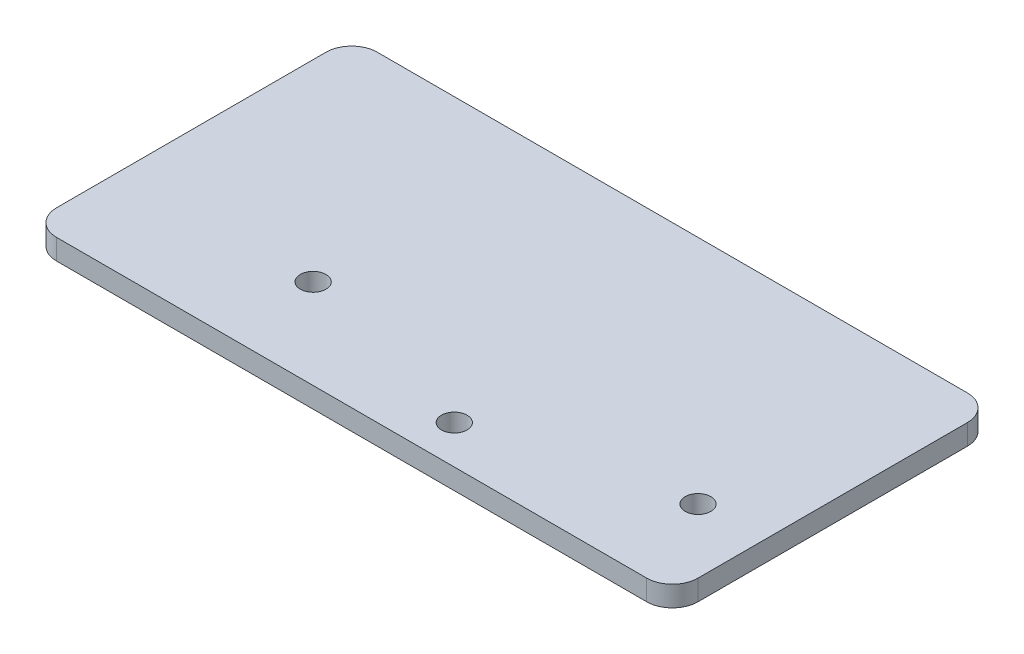
SolidWorks part; units mm, degrees
material "A-玻璃纤维"
ref_plane "前视基准面" through (0, 0, 0) normal (0, 0, 1) x (1, 0, 0)
ref_plane "上视基准面" through (0, 0, 0) normal (0, 1, 0) x (1, 0, 0)
ref_plane "右视基准面" through (0, 0, 0) normal (1, 0, 0) x (0, 0, -1)
other "Configuration Table"
sketch "草图1" plane through (0, 0, 0) normal (0, 1, 0) x (1, 0, 0)
  line L0 (-10, -5.5) -> (38.4981, -5.5) construction
  line L1 (-25, -12.5) -> (25, -12.5)
  line L2 (-25, -12.5) -> (-25, 12.5)
  line L3 (-25, 12.5) -> (25, 12.5)
  line L4 (25, -12.5) -> (25, 12.5)
  line L5 (-25, -12.5) -> (25, 12.5) construction
  line L6 (-25, 12.5) -> (25, -12.5) construction
  circle A0 centre (-10, -5.5) radius 1
  circle A1 centre (20, -5.5) radius 1
  circle A2 centre (5, -9.5) radius 1
  point P0 (0, 0)
  dimension "D3" = 2
  dimension "D4" = 2
  dimension "D5" = 30
  dimension "D6" = 15
  dimension "D7" = 18
  dimension "D8" = 2
  dimension "D9" = 30
  dimension "D10" = 22
  dimension "D1" = 50
  dimension "D2" = 25
extrude "凸台-拉伸1" add sketch "草图1" along normal blind 1.6
fillet "圆角1" radius 2 4 edges at (-25, 0.8, -12.5) (-25, 0.8, 12.5) (25, 0.8, -12.5) (25, 0.8, 12.5)
